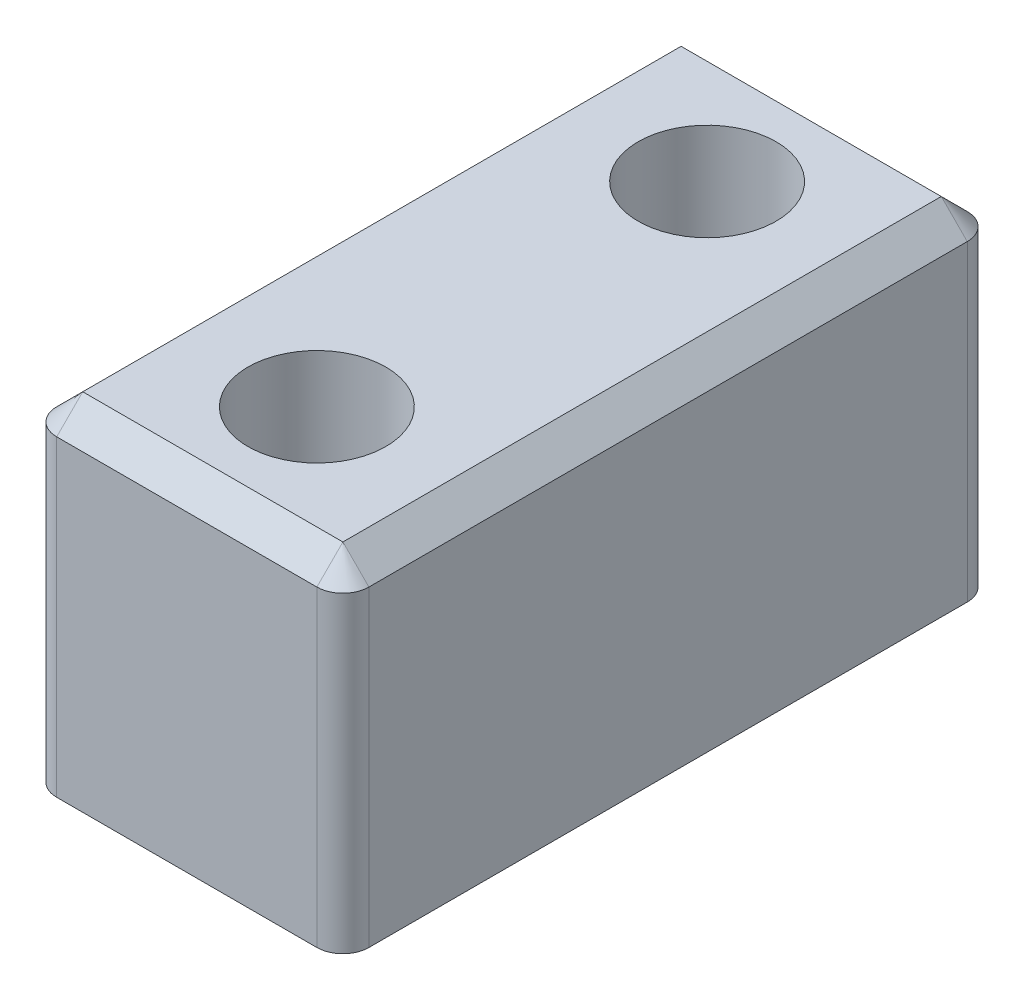
SolidWorks part; units mm, degrees
ref_plane "Front Plane" through (0, 0, 0) normal (0, 0, 1) x (1, 0, 0)
ref_plane "Top Plane" through (0, 0, 0) normal (0, 1, 0) x (1, 0, 0)
ref_plane "Right Plane" through (0, 0, 0) normal (1, 0, 0) x (0, 0, -1)
sketch "Sketch1" plane through (0, 0, 0) normal (0, 1, 0) x (1, 0, 0)
  line L0 (0, 7.5) -> (0, -7.5) construction
  line L1 (-6, 12.5) -> (6, 12.5)
  line L2 (-6, 12.5) -> (-6, -12.5)
  line L3 (-6, -12.5) -> (6, -12.5)
  line L4 (6, 12.5) -> (6, -12.5)
  line L5 (-6, 12.5) -> (6, -12.5) construction
  line L6 (-6, -12.5) -> (6, 12.5) construction
  circle A0 centre (0, 7.5) radius 2.65
  circle A1 centre (0, -7.5) radius 2.65
  point P0 (0, 0)
  dimension "D2" = 5.3
  dimension "D3" = 15
  dimension "D5" = 5.3
  dimension "D1" = 25
  dimension "D4" = 12
extrude "Boss-Extrude1" add sketch "Sketch1" along normal mid plane 13
fillet "Fillet1" radius 1 4 edges at (-6, 0, 12.5) (-6, 0, -12.5) (6, 0, -12.5) (6, 0, 12.5)
chamfer "Chamfer1" distance 1 angle 45 8 edges at (0, 6.5, -12.5) (-5.7071, 6.5, -12.2071) (5.7071, 6.5, -12.2071) (-6, 6.5, 0) (6, 6.5, 0) (-5.7071, 6.5, 12.2071) (5.7071, 6.5, 12.2071) (0, 6.5, 12.5)
